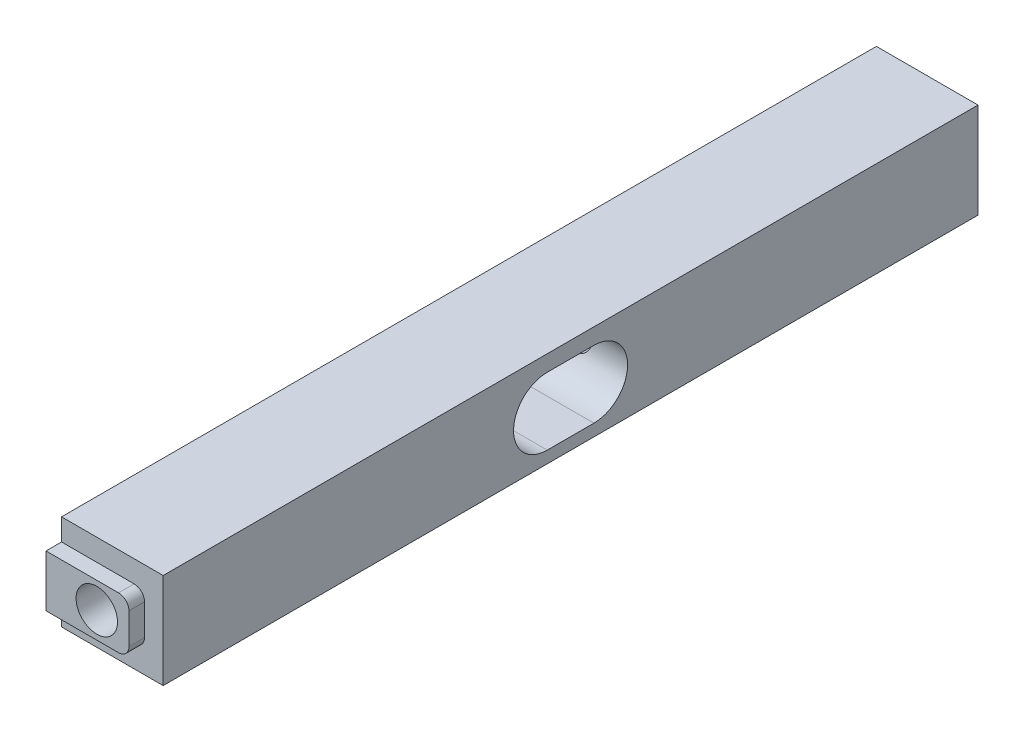
SolidWorks part; units mm, degrees
ref_plane "Front Plane" through (0, 0, 0) normal (0, 0, 1) x (1, 0, 0)
ref_plane "Top Plane" through (0, 0, 0) normal (0, 1, 0) x (1, 0, 0)
ref_plane "Right Plane" through (0, 0, 0) normal (1, 0, 0) x (0, 0, -1)
sketch "Sketch1" plane through (0, 0, 0) normal (1, 0, 0) x (0, 0, -1)
  line L0 (0, 4.6) -> (0, -4.6) construction
  line L1 (-40.8, 4.6) -> (40.8, 4.6)
  line L2 (-40.8, 4.6) -> (-40.8, -4.6)
  line L3 (-40.8, -4.6) -> (40.8, -4.6)
  line L4 (40.8, 4.6) -> (40.8, -4.6)
  line L5 (-40.8, 4.6) -> (40.8, -4.6) construction
  line L6 (-40.8, -4.6) -> (40.8, 4.6) construction
  line L9 (-40.8, -0.2) -> (40.8, -0.2) construction
  line L10 (-40.8, 3.7) -> (40.8, 3.7)
  line L11 (-40.8, 3.7) -> (-40.8, -3.7)
  line L12 (-40.8, -3.7) -> (40.8, -3.7)
  line L13 (40.8, 3.7) -> (40.8, -3.7)
  line L14 (-40.8, 3.7) -> (40.8, -3.7) construction
  line L15 (-40.8, -3.7) -> (40.8, 3.7) construction
  line L16 (-2.25, -0.2) -> (2.25, -0.2) construction
  line L17 (-2.25, 3.05) -> (2.25, 3.05)
  line L18 (-2.25, -3.45) -> (2.25, -3.45)
  arc A2 (-2.25, 3.05) -> (-2.25, -3.45) centre (-2.25, -0.2) ccw
  arc A3 (2.25, -3.45) -> (2.25, 3.05) centre (2.25, -0.2) ccw
  point P0 (0, 0)
  point P8 (0, 0)
  point P15 (0, 0)
  point P18 (0, -0.2)
  point P20 (0, 0)
  point P24 (-5.5, -0.2)
  point P25 (5.5, -0.2)
  point P26 (0, 0)
  point P27 (-2.25, -0.2)
  point P28 (0, 0)
  point P29 (0, 0)
  dimension "D1" = 81.6
  dimension "D2" = 9.2
  dimension "D3" = 7.4
  dimension "D4" = 3.5
  dimension "D5" = 11
  dimension "D6" = 6.5
extrude "Boss-Extrude1" add sketch "Sketch1" along normal blind 9.8 contours L2 L10 L4 L1 | L2 L12 L4 L10 A3 L18 A2 L17 | L12 L2 L3 L4
sketch "Sketch5" plane through (0, 0, 40.8) normal (0, 0, 1) x (1, 0, 0)
  line L0 (0, 0) -> (9.8, 0) construction
  line L3 (7, 2.5) -> (0, 2.5)
  line L4 (8, 1.5) -> (8, -1.5)
  line L5 (7, -2.5) -> (0, -2.5)
  line L6 (0, 2.5) -> (0, -2.5)
  line L7 (8, 2.5) -> (0, -2.5) construction
  line L8 (8, -2.5) -> (0, 2.5) construction
  line L9 (9.8, 4.6) -> (9.8, -4.6) construction
  line L10 (0, 4.6) -> (0, -4.6) construction
  line L13 (0, 4.6) -> (0, -4.6)
  line L14 (0, -4.6) -> (9.8, -4.6)
  line L15 (0, 4.6) -> (0, -4.6)
  line L16 (9.8, 4.6) -> (0, 4.6)
  line L18 (0, -4.6) -> (9.8, -4.6)
  line L20 (9.8, 4.6) -> (0, 4.6)
  line L21 (9.8, -4.6) -> (9.8, 4.6)
  line L22 (9.8, -4.6) -> (9.8, 4.6)
  arc A0 (8, -1.5) -> (7, -2.5) centre (7, -1.5) cw
  arc A1 (7, 2.5) -> (8, 1.5) centre (7, 1.5) cw
  point P3 (9.8, 0)
  point P5 (4, 0)
  point P11 (0, -2.5)
  dimension "D3" = 1
  dimension "D1" = 5
  dimension "D2" = 8
  dimension "D4" = 0
extrude "Cut-Extrude3" cut sketch "Sketch5" against normal blind 1.5
sketch "Sketch3" plane through (0, 0, 40.8) normal (0, 0, 1) x (1, 0, 0)
  line L0 (0, 2.5) -> (9.8, -2.5) construction
  line L2 (0, -2.5) -> (9.8, -2.5) construction
  line L4 (7, 2.5) -> (0, 2.5) construction
  line L5 (7, 2.5) -> (0, 2.5) construction
  line L6 (0, 2.5) -> (0, -2.5) construction
  line L7 (9.8, -4.6) -> (9.8, 4.6) construction
  circle A0 centre (4.9, 0) radius 1.45
  point P6 (9.8, -2.5)
  point P7 (0, 2.5)
  point P12 (9.8, -2.5112)
  point P13 (9.8, -2.5)
  point P14 (0, 2.5)
  point P21 (0, -2.5)
  dimension "D1" = 2.9
extrude "Cut-Extrude1" cut sketch "Sketch3" against normal up to next
sketch "Sketch4" plane through (0, 0, 40.8) normal (0, 0, 1) x (1, 0, 0)
  circle A0 centre (4.9, 0) radius 2
  dimension "D1" = 4
extrude "Cut-Extrude2" cut sketch "Sketch4" against normal offset from surface (27.3018 mm away) 8 up to face at (3.4622, -0.1876, 5.5)
mirror "Mirror5" about plane through (0, 0, 0) normal (0, 0, 1) of "Cut-Extrude3", "Cut-Extrude1", "Cut-Extrude2"
